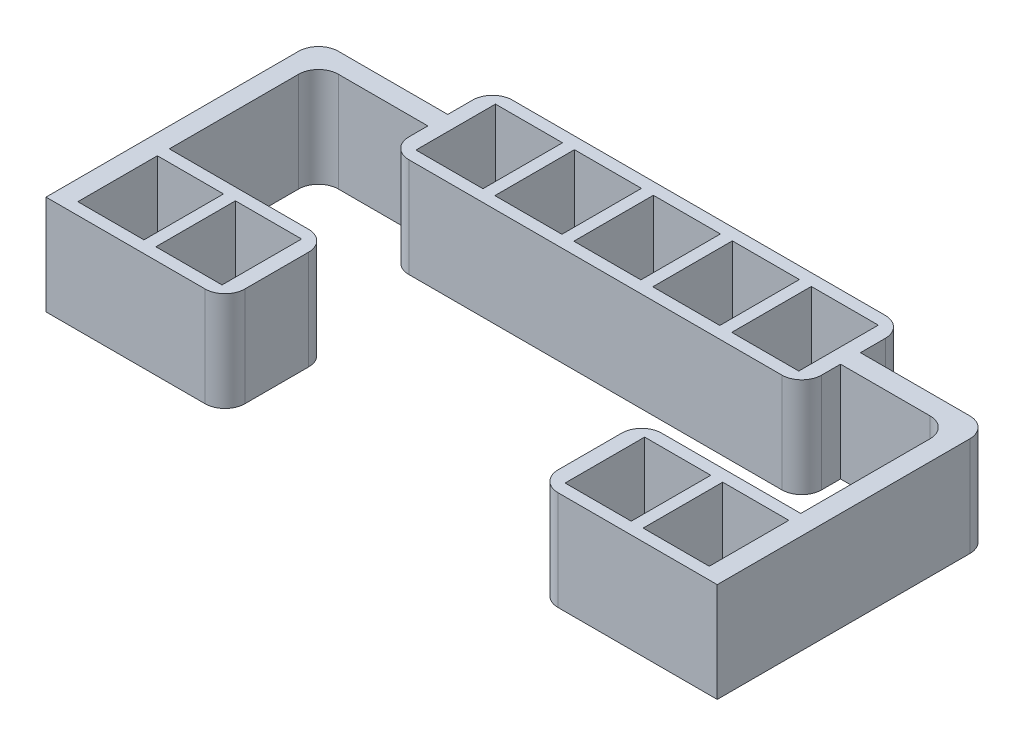
SolidWorks part; units mm, degrees
ref_plane "Plano frontal" through (0, 0, 0) normal (0, 0, 1) x (1, 0, 0)
ref_plane "Plano superior" through (0, 0, 0) normal (0, 1, 0) x (1, 0, 0)
ref_plane "Plano direito" through (0, 0, 0) normal (1, 0, 0) x (0, 0, -1)
sketch "Esboço1" plane through (0, 0, 0) normal (0, 1, 0) x (1, 0, 0)
  line L0 (-12.51, 4) -> (-19.25, 4)
  line L1 (19.25, -4) -> (12.51, -4)
  line L2 (19.25, -4) -> (19.25, 4)
  line L3 (19.25, 4) -> (12.51, 4)
  line L4 (-19.25, -4) -> (-19.25, 4)
  line L5 (19.25, -4) -> (12.51, -2.5995) construction
  line L6 (19.25, 4) -> (12.51, 2.5995) construction
  line L7 (-18.75, 5.2) -> (18.75, 5.2)
  line L8 (-20.75, 3.2) -> (-20.75, -3.2)
  line L9 (-18.75, -5.2) -> (18.75, -5.2)
  line L10 (20.75, 3.2) -> (20.75, -3.2)
  line L11 (-19.25, 4) -> (-12.51, 4)
  line L12 (-19.25, 4) -> (-19.25, -4)
  line L13 (-19.25, -4) -> (-12.51, -4)
  line L14 (-12.51, 4) -> (-12.51, -4)
  line L15 (-11.31, 4) -> (-4.57, 4)
  line L16 (-11.31, 4) -> (-11.31, -4)
  line L17 (-11.31, -4) -> (-4.57, -4)
  line L18 (-4.57, 4) -> (-4.57, -4)
  line L19 (-3.37, 4) -> (3.37, 4)
  line L20 (-3.37, 4) -> (-3.37, -4)
  line L21 (-3.37, -4) -> (3.37, -4)
  line L22 (3.37, 4) -> (3.37, -4)
  line L23 (4.57, 4) -> (11.31, 4)
  line L24 (4.57, 4) -> (4.57, -4)
  line L25 (4.57, -4) -> (11.31, -4)
  line L26 (11.31, 4) -> (11.31, -4)
  line L27 (12.51, 4) -> (19.25, 4)
  line L28 (12.51, 4) -> (12.51, -4)
  line L29 (12.51, -4) -> (19.25, -4)
  line L30 (19.25, 4) -> (19.25, -4)
  line L31 (-12.51, 2.5995) -> (-19.25, 4) construction
  line L32 (-12.51, -2.5995) -> (-19.25, -4) construction
  line L33 (-12.51, -4) -> (-19.25, -4)
  line L34 (-4.57, 4) -> (-11.31, 4)
  line L35 (-4.57, 0.9496) -> (-11.31, 2.3501) construction
  line L36 (-4.57, -0.9496) -> (-11.31, -2.3501) construction
  line L37 (-4.57, -4) -> (-11.31, -4)
  line L38 (3.37, 4) -> (-3.37, 4)
  line L39 (3.37, 0.7003) -> (-3.37, -0.7003) construction
  line L40 (3.37, -0.7003) -> (-3.37, 0.7003) construction
  line L41 (3.37, -4) -> (-3.37, -4)
  line L42 (11.31, 4) -> (4.57, 4)
  line L43 (11.31, 2.3501) -> (4.57, 0.9496) construction
  line L44 (11.31, -2.3501) -> (4.57, -0.9496) construction
  line L45 (11.31, -4) -> (4.57, -4)
  line L46 (-20.75, 3.2) -> (-20.75, 0.7)
  line L47 (0, 0) -> (0, 2.3377)
  line L48 (-33.75, -26.7) -> (-33.75, -1.3)
  line L49 (-20.75, 0.7) -> (-20.75, -1.3)
  line L50 (-20.75, -1.3) -> (-29.75, -1.3)
  line L51 (-31.75, 0.7) -> (-20.75, 0.7)
  line L52 (-33.75, -26.7) -> (-33.75, -16)
  line L53 (-23.9, -17.5) -> (-17.25, -17.5)
  line L54 (15.75, -18.3) -> (15.75, -24.7)
  line L55 (-33.75, -16) -> (-33.75, -16.3)
  line L56 (-31.75, -3.3) -> (-31.75, -16)
  line L57 (-33.75, -16) -> (-33.75, -17.5)
  line L58 (-31.75, -17.5) -> (-25.1, -17.5)
  line L59 (-31.75, -17.5) -> (-31.75, -25.5)
  line L60 (-23.9, -25.5) -> (-17.25, -25.5)
  line L61 (33.75, -26.7) -> (17.75, -26.7)
  line L62 (-33.75, -26.7) -> (-33.75, -14.6427)
  line L63 (-17.25, -17.5) -> (-17.25, -25.5)
  line L64 (-31.75, -16.3) -> (-17.75, -16.3)
  line L65 (-33.75, -16.3) -> (-33.75, -26.7)
  line L66 (-25.1, -25.5) -> (-25.1, -17.5)
  line L67 (-33.75, -26.7) -> (-33.75, -25.5)
  line L68 (-23.9, -25.5) -> (-23.9, -17.5)
  line L69 (-31.75, -25.5) -> (-25.1, -25.5)
  line L70 (31.75, -25.5) -> (25.1, -25.5)
  line L71 (23.9, -25.5) -> (23.9, -17.5)
  line L72 (33.75, -26.7) -> (33.75, -25.5)
  line L73 (25.1, -25.5) -> (25.1, -17.5)
  line L74 (33.75, -16.3) -> (33.75, -26.7)
  line L75 (31.75, -16.3) -> (17.75, -16.3)
  line L76 (17.25, -17.5) -> (17.25, -25.5)
  line L77 (33.75, -26.7) -> (33.75, -14.6427)
  line L78 (23.9, -25.5) -> (17.25, -25.5)
  line L79 (31.75, -17.5) -> (31.75, -25.5)
  line L80 (31.75, -17.5) -> (25.1, -17.5)
  line L81 (33.75, -16) -> (33.75, -17.5)
  line L82 (31.75, -3.3) -> (31.75, -16)
  line L83 (33.75, -16) -> (33.75, -16.3)
  line L84 (23.9, -17.5) -> (17.25, -17.5)
  line L85 (33.75, -26.7) -> (33.75, -16)
  line L86 (33.75, -26.7) -> (33.75, -1.3)
  line L87 (31.75, -16) -> (31.75, -16.3)
  line L88 (29.75, -1.3) -> (20.75, -1.3)
  line L89 (31.75, 0.7) -> (20.75, 0.7)
  line L90 (-31.75, -16) -> (-31.75, -16.3)
  line L91 (-33.75, -26.7) -> (-17.75, -26.7)
  line L92 (-15.75, -18.3) -> (-15.75, -24.7)
  arc A0 (18.75, -5.2) -> (20.75, -3.2) centre (18.75, -3.2) ccw
  arc A1 (18.75, 5.2) -> (20.75, 3.2) centre (18.75, 3.2) cw
  arc A2 (-18.75, 5.2) -> (-20.75, 3.2) centre (-18.75, 3.2) ccw
  arc A3 (-20.75, -3.2) -> (-18.75, -5.2) centre (-18.75, -3.2) ccw
  arc A4 (-31.75, -3.3) -> (-29.75, -1.3) centre (-29.75, -3.3) cw
  arc A5 (-33.75, -1.3) -> (-31.75, 0.7) centre (-31.75, -1.3) cw
  arc A6 (33.75, -1.3) -> (31.75, 0.7) centre (31.75, -1.3) ccw
  arc A7 (31.75, -3.3) -> (29.75, -1.3) centre (29.75, -3.3) ccw
  arc A8 (17.75, -16.3) -> (15.75, -18.3) centre (17.75, -18.3) ccw
  arc A9 (17.75, -26.7) -> (15.75, -24.7) centre (17.75, -24.7) cw
  arc A10 (-17.75, -26.7) -> (-15.75, -24.7) centre (-17.75, -24.7) ccw
  arc A11 (-17.75, -16.3) -> (-15.75, -18.3) centre (-17.75, -18.3) cw
  point P0 (0, 0)
  point P1 (0, 0)
  point P6 (0, 0)
  point P12 (0, 0)
  point P108 (15.75, -16)
  point P109 (15.75, -27)
  point P110 (15.75, -26.7)
  point P116 (-15.75, -26.7)
  point P117 (-15.75, -27)
  point P120 (-15.75, -16)
  dimension "D15" = 2
  dimension "D18" = 2
  dimension "D28" = 2
  dimension "D1" = 38.5
  dimension "D2" = 8
  dimension "D3" = 1.2
  dimension "D4" = 1.5
  dimension "D5" = 1.2
  dimension "D6" = 1.5
  dimension "D7" = 6.74
  dimension "D8" = 6.74
  dimension "D9" = 1.2
  dimension "D10" = 1.2
  dimension "D11" = 1.2
  dimension "D12" = 1.2
  dimension "D13" = 6.74
  dimension "D14" = 6.74
  dimension "D16" = 2.5
  dimension "D17" = 2
  dimension "D22" = 1.2
  dimension "D23" = 2
  dimension "D24" = 0.3
  dimension "D25" = 8
  dimension "D26" = 18
  dimension "D27" = 6.65
  dimension "D29" = 6.65
  dimension "D31" = 13
extrude "Ressalto-extrusão1" add sketch "Esboço1" along normal blind 10
